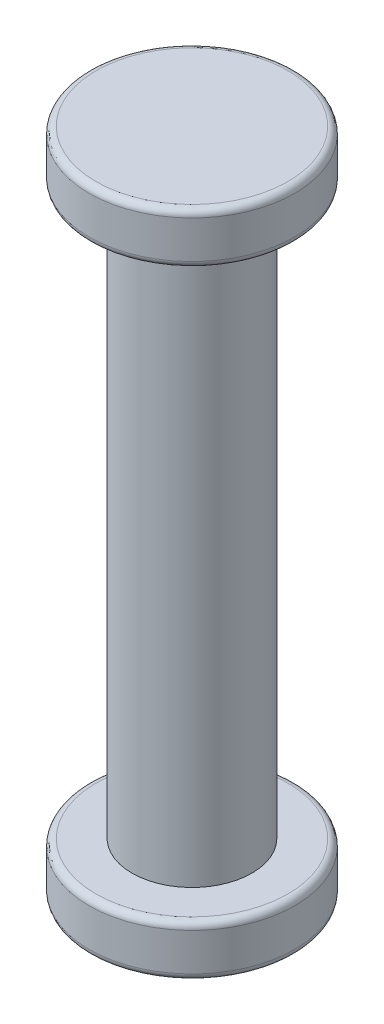
SolidWorks part; units mm, degrees
ref_plane "Front Plane" through (0, 0, 0) normal (0, 0, 1) x (1, 0, 0)
ref_plane "Top Plane" through (0, 0, 0) normal (0, 1, 0) x (1, 0, 0)
ref_plane "Right Plane" through (0, 0, 0) normal (1, 0, 0) x (0, 0, -1)
sketch "Sketch1" plane through (0, 0, 0) normal (0, 1, 0) x (1, 0, 0)
  circle A0 centre (0, 0) radius 1.75
  dimension "D1" = 3.5
extrude "Boss-Extrude1" add sketch "Sketch1" along normal mid plane 16.5
sketch "Sketch2" plane through (0, 0, 0) normal (0, 0, 1) x (1, 0, 0)
  line L0 (0, 8.25) -> (-2.8, 8.25)
  line L1 (1.75, 8.25) -> (-1.75, 8.25) construction
  line L2 (-3, 8.45) -> (-3, 9.55)
  line L3 (-2.8, 9.75) -> (0, 9.75)
  line L4 (0, 0) -> (3.415, 0) construction
  line L5 (-2.8, -9.75) -> (0, -9.75)
  line L6 (-3, -8.45) -> (-3, -9.55)
  line L7 (0, -8.25) -> (-2.8, -8.25)
  line L8 (0, 9.75) -> (0, -9.75)
  arc A0 (-3, -9.55) -> (-2.8, -9.75) centre (-2.8, -9.55) ccw
  arc A1 (-3, -8.45) -> (-2.8, -8.25) centre (-2.8, -8.45) cw
  arc A2 (-3, 8.45) -> (-2.8, 8.25) centre (-2.8, 8.45) ccw
  arc A3 (-3, 9.55) -> (-2.8, 9.75) centre (-2.8, 9.55) cw
  point P13 (0, 9.5973)
  point P14 (0, 0)
  point P17 (-3, -9.75)
  point P20 (-3, -8.25)
  point P23 (-3, 8.25)
  point P26 (-3, 9.75)
  dimension "D3" = 0.2
  dimension "D1" = 3
  dimension "D2" = 1.5
revolve "Revolve2" add sketch "Sketch2" angle 360 about L8
